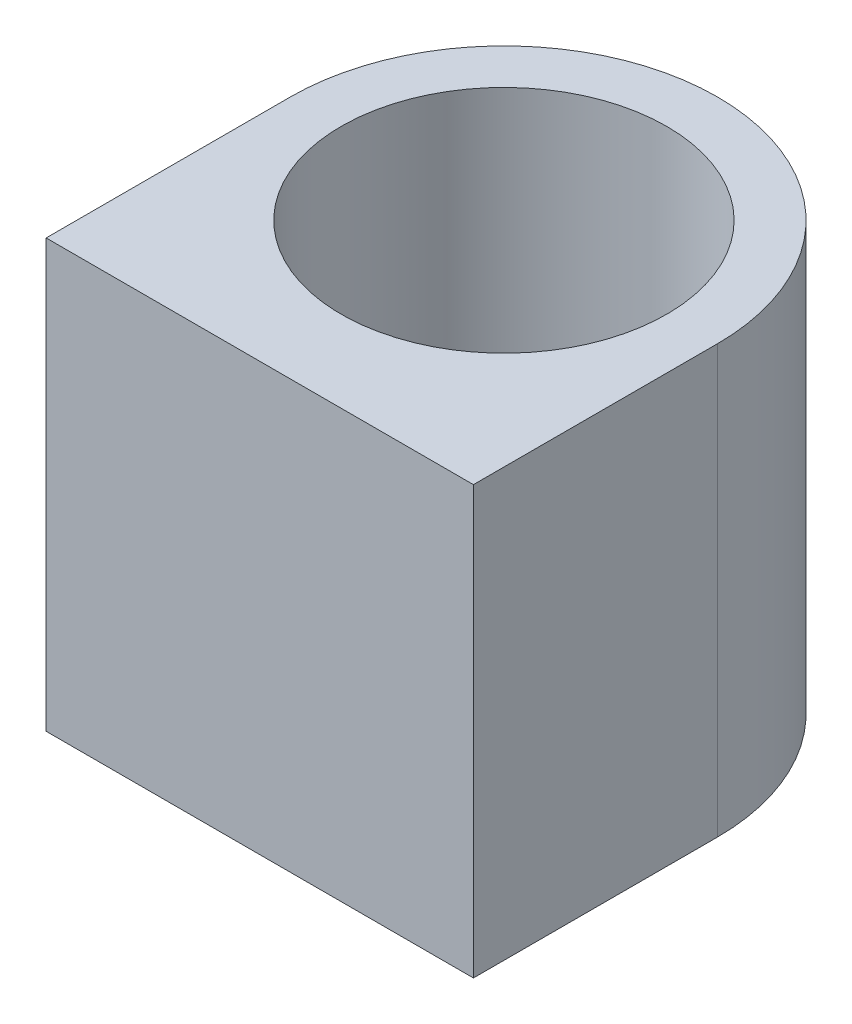
SolidWorks part; units mm, degrees
material "Thornel Mat VMA"
ref_plane "Front Plane" through (0, 0, 0) normal (0, 0, 1) x (1, 0, 0)
ref_plane "Top Plane" through (0, 0, 0) normal (0, 1, 0) x (1, 0, 0)
ref_plane "Right Plane" through (0, 0, 0) normal (1, 0, 0) x (0, 0, -1)
sketch "Sketch1" plane through (0, 0, 0) normal (0, 1, 0) x (1, 0, 0)
  line L0 (-10.5, 0) -> (-10.5, -12)
  line L1 (-10.5, -12) -> (10.5, -12)
  line L2 (10.5, -12) -> (10.5, 0)
  line L3 (-10.5, 0) -> (10.5, 0) construction
  circle A0 centre (0, 0) radius 8
  arc A1 (-10.5, 0) -> (10.5, 0) centre (0, 0) cw
  dimension "D1" = 16
  dimension "D2" = 2.5
  dimension "D3" = 12
extrude "Boss-Extrude1" add sketch "Sketch1" along normal blind 21
